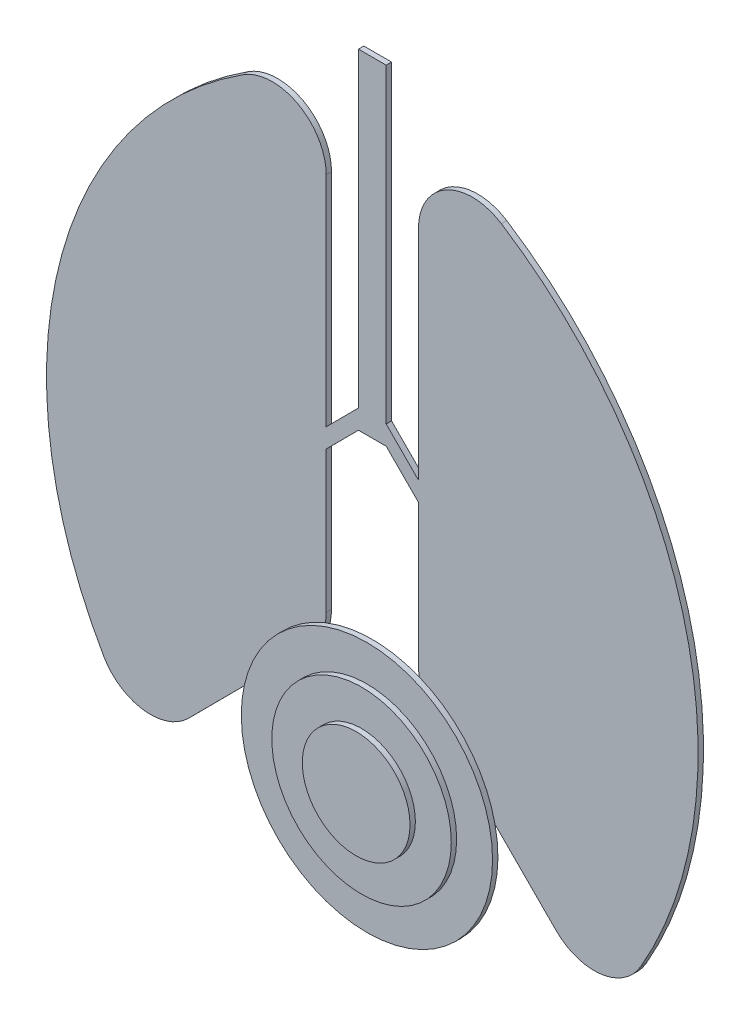
SolidWorks part; units mm, degrees
ref_plane "Front Plane" through (0, 0, 0) normal (0, 0, 1) x (1, 0, 0)
ref_plane "Top Plane" through (0, 0, 0) normal (0, 1, 0) x (1, 0, 0)
ref_plane "Right Plane" through (0, 0, 0) normal (1, 0, 0) x (0, 0, -1)
sketch "Sketch3" plane through (0, 0, 0) normal (0, 0, 1) x (1, 0, 0)
  line L0 (0, 94.186) -> (0, -105.814) construction
  line L1 (-7.733, 171.9454) -> (-7.733, 79.7326)
  line L2 (-7.733, 79.7326) -> (-25.7273, 61.6477)
  line L3 (-7.733, 69.0009) -> (-25.7273, 50.9161)
  line L4 (-7.733, 69.0009) -> (7.733, 69.0009)
  line L5 (-25.7273, 61.6477) -> (-25.7273, 183.2326)
  line L6 (-25.7273, 50.9161) -> (-25.7273, -27.8882)
  line L7 (-34.4609, -49.0482) -> (-102.3521, -117.2809)
  line L8 (34.4609, -49.0482) -> (102.3521, -117.2809)
  line L9 (25.7273, 50.9161) -> (25.7273, -27.8882)
  line L10 (25.7273, 61.6477) -> (25.7273, 183.2326)
  line L11 (7.733, 69.0009) -> (25.7273, 50.9161)
  line L12 (7.733, 79.7326) -> (25.7273, 61.6477)
  line L13 (7.733, 171.9454) -> (7.733, 79.7326)
  line L14 (-7.733, 171.9454) -> (-7.733, 252.9115)
  line L15 (-7.733, 252.9115) -> (7.733, 252.9115)
  line L16 (7.733, 252.9115) -> (7.733, 171.9454)
  arc A0 (-71.9156, 208.49) -> (-149.5931, -111.1316) centre (56.5764, 8.0129) ccw
  arc A1 (-102.3521, -117.2809) -> (-149.5931, -111.1316) centre (-123.6185, -96.1209) cw
  arc A2 (-25.7273, -27.8882) -> (-34.4609, -49.0482) centre (-55.7273, -27.8882) cw
  arc A3 (-25.7273, 183.2326) -> (-71.9156, 208.49) centre (-55.7273, 183.2326) ccw
  arc A4 (25.7273, 183.2326) -> (71.9156, 208.49) centre (55.7273, 183.2326) cw
  arc A5 (25.7273, -27.8882) -> (34.4609, -49.0482) centre (55.7273, -27.8882) ccw
  arc A6 (102.3521, -117.2809) -> (149.5931, -111.1316) centre (123.6185, -96.1209) ccw
  arc A7 (71.9156, 208.49) -> (149.5931, -111.1316) centre (-56.5764, 8.0129) cw
  point P34 (0, 69.0009)
extrude "Boss-Extrude2" add sketch "Sketch3" against normal blind 3
sketch "Sketch4" plane through (0, 0, 0) normal (0, 0, 1) x (1, 0, 0)
  circle A0 centre (0, -98.0316) radius 70
  dimension "D1" = 140
extrude "Boss-Extrude3" add sketch "Sketch4" along normal blind 3
sketch "Sketch5" plane through (0, 0, 3) normal (0, 0, 1) x (1, 0, 0)
  circle A0 centre (0, -98.0316) radius 50
  dimension "D1" = 100
extrude "Boss-Extrude4" add sketch "Sketch5" along normal blind 3
sketch "Sketch6" plane through (0, 0, 6) normal (0, 0, 1) x (1, 0, 0)
  circle A0 centre (0, -98.0316) radius 30
  dimension "D1" = 60
extrude "Boss-Extrude5" add sketch "Sketch6" along normal blind 3
